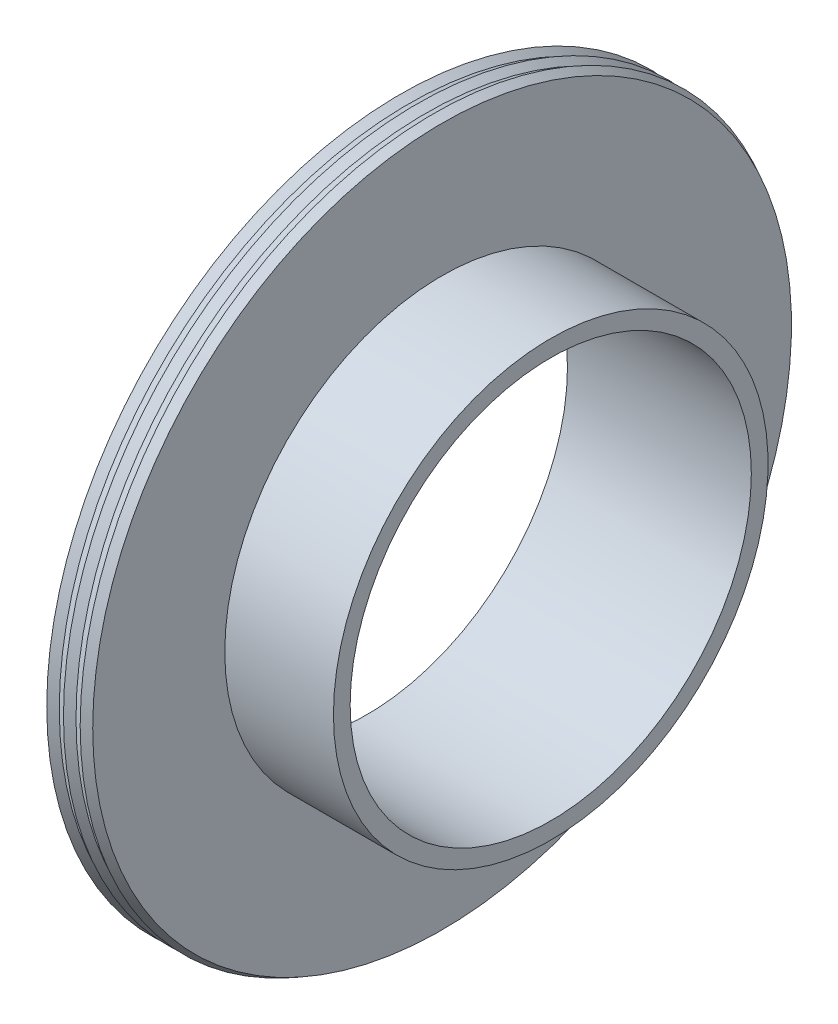
SolidWorks part; units mm, degrees
ref_plane "前视基准面" through (0, 0, 0) normal (0, 0, 1) x (1, 0, 0)
ref_plane "上视基准面" through (0, 0, 0) normal (0, 1, 0) x (1, 0, 0)
ref_plane "右视基准面" through (0, 0, 0) normal (1, 0, 0) x (0, 0, -1)
other "Configuration Table"
sketch "草图1" plane through (0, 0, 0) normal (0, 0, 1) x (1, 0, 0)
  line L0 (-59.6593, 0) -> (89.3294, 0) construction
  line L1 (0, 0) -> (0, 24)
  line L2 (0, 24) -> (22, 24)
  line L3 (22, 24) -> (22, 26)
  line L4 (22, 26) -> (0, 26)
  line L5 (0, 26) -> (0, 24)
  line L6 (0, 0) -> (0, 2.3)
  line L7 (0, 2.3) -> (0, 26)
  line L9 (4, 42.3) -> (9, 42.3)
  line L10 (9, 42.3) -> (9, 26)
  line L11 (9, 26) -> (4, 26)
  line L12 (4, 26) -> (4, 42.3)
  line L14 (4, 42.3) -> (5, 41.8)
  line L15 (5, 41.8) -> (6, 42.3)
  line L16 (6, 42.3) -> (7, 41.8)
  line L17 (7, 41.8) -> (8, 42.3)
  line L18 (8, 42.3) -> (9, 41.8)
  line L20 (9, 41.8) -> (10, 42.3) [skipped]
  dimension "D1" = 24
  dimension "D2" = 2
  dimension "D3" = 22
  dimension "D4" = 5
  dimension "D5" = 16.3
  dimension "D8" = 1
  dimension "D9" = 3
revolve "旋转1" add sketch "草图1" angle 360 about L0
